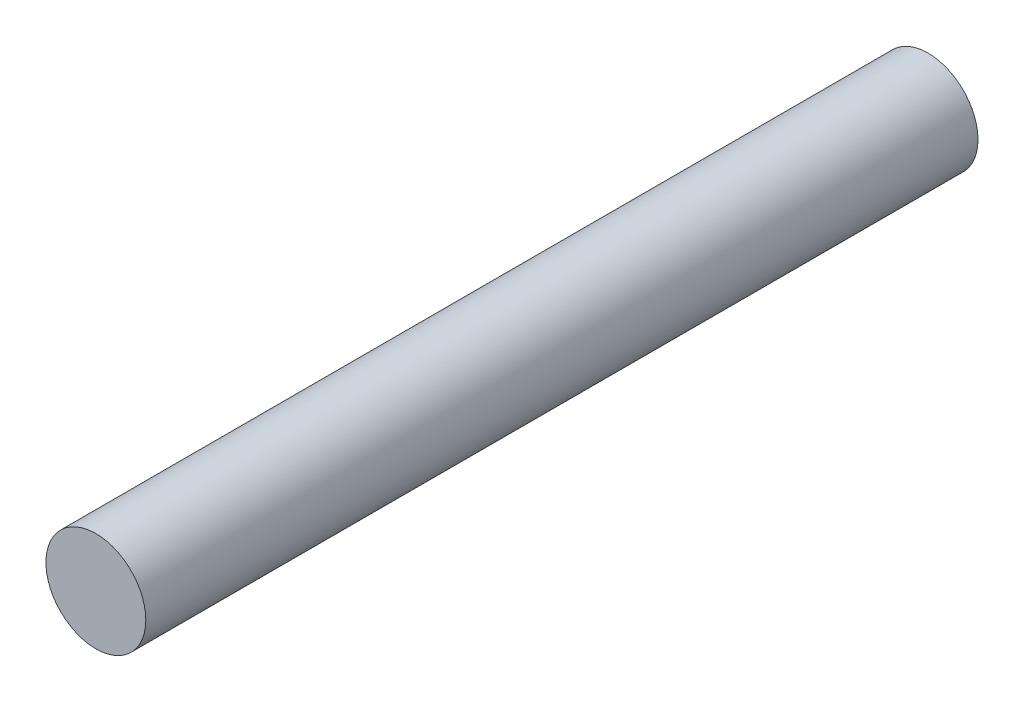
SolidWorks part; units mm, degrees
material "普通碳钢"
ref_plane "前视" through (0, 0, 0) normal (0, 0, 1) x (1, 0, 0)
ref_plane "上视" through (0, 0, 0) normal (0, 1, 0) x (1, 0, 0)
ref_plane "右视" through (0, 0, 0) normal (1, 0, 0) x (0, 0, -1)
sketch "草图1" plane through (0, 0, 0) normal (0, 0, 1) x (1, 0, 0)
  circle A0 centre (0, 0) radius 1.5
  dimension "D1" = 3
extrude "凸台-拉伸1" add sketch "草图1" along normal mid plane 25
